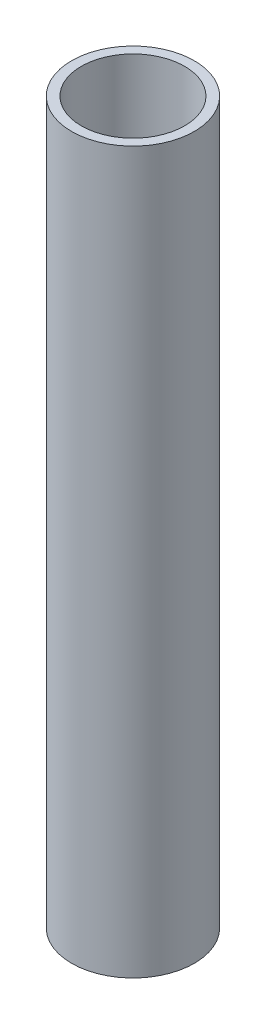
SolidWorks part; units mm, degrees
ref_plane "Front Plane" through (0, 0, 0) normal (0, 0, 1) x (1, 0, 0)
ref_plane "Top Plane" through (0, 0, 0) normal (0, 1, 0) x (1, 0, 0)
ref_plane "Right Plane" through (0, 0, 0) normal (1, 0, 0) x (0, 0, -1)
sketch "Sketch1" plane through (0, 0, 0) normal (0, 1, 0) x (1, 0, 0)
  circle A0 centre (0, 0) radius 25.4
  circle A1 centre (0, 0) radius 30.1625
  dimension "D1" = 50.8
  dimension "D2" = 60.325
extrude "Boss-Extrude1" add sketch "Sketch1" along normal mid plane 354.33
